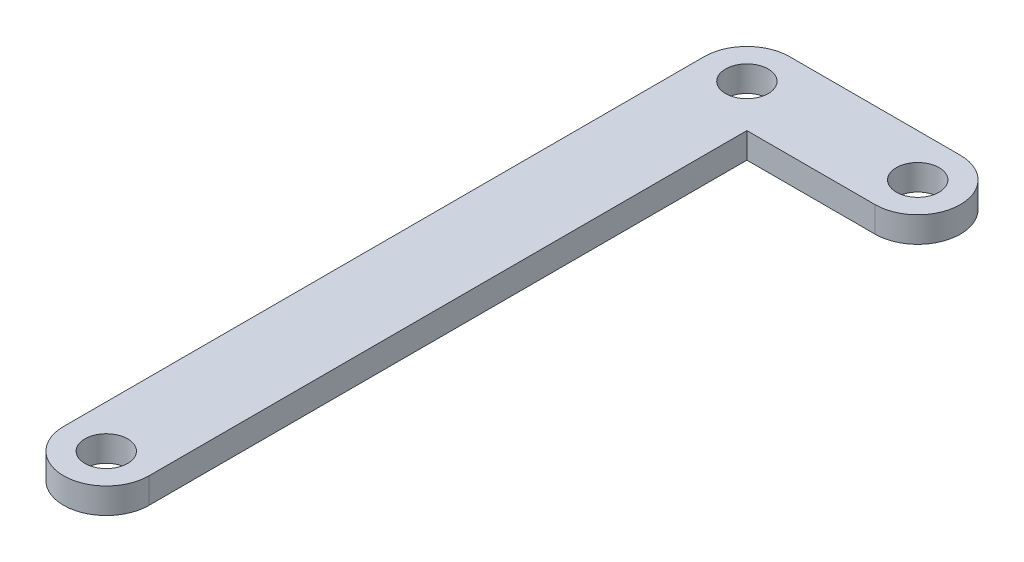
SolidWorks part; units mm, degrees
ref_plane "Front Plane" through (0, 0, 0) normal (0, 0, 1) x (1, 0, 0)
ref_plane "Top Plane" through (0, 0, 0) normal (0, 1, 0) x (1, 0, 0)
ref_plane "Right Plane" through (0, 0, 0) normal (1, 0, 0) x (0, 0, -1)
sketch "Sketch1" plane through (0, 0, 0) normal (0, 1, 0) x (1, 0, 0)
  line L7 (19.0688, -48.4258) -> (19.0688, 26.5742)
  line L8 (19.0688, 26.5742) -> (29.0688, 26.5742)
  line L9 (29.0688, -48.4258) -> (29.0688, 26.5742)
  line L10 (24.0688, 31.5742) -> (44.0688, 31.5742)
  line L11 (24.0688, 31.5742) -> (24.0688, 21.5742)
  line L12 (24.0688, 21.5742) -> (44.0688, 21.5742)
  arc A5 (19.0688, -48.4258) -> (29.0688, -48.4258) centre (24.0688, -48.4258) ccw
  circle A6 centre (24.0688, -48.4258) radius 2.5
  arc A7 (44.0688, 31.5742) -> (44.0688, 21.5742) centre (44.0688, 26.5742) cw
  circle A8 centre (44.0688, 26.5742) radius 2.5
  arc A9 (24.0688, 31.5742) -> (19.0688, 26.5742) centre (24.0688, 26.5742) ccw
  circle A10 centre (24.0688, 26.5742) radius 2.5
  point P17 (29.0688, 21.5742)
  point P24 (29.0688, 21.5742)
  dimension "D4" = 75
  dimension "D7" = 5
  dimension "D11" = 5
  dimension "D13" = 5
  dimension "D6" = 10
  dimension "D8" = 70
  dimension "D9" = 20
  dimension "D10" = 10
  dimension "D12" = 15
extrude "Boss-Extrude1" add sketch "Sketch1" along normal blind 3 contours A10 L8 L7 A5 L9 L12 L11 A6 | A10 L8 L9 L12 A7 L10 L11 A8 | A10 L11 L12 L9 L8 | A10 L11 A9 L8
